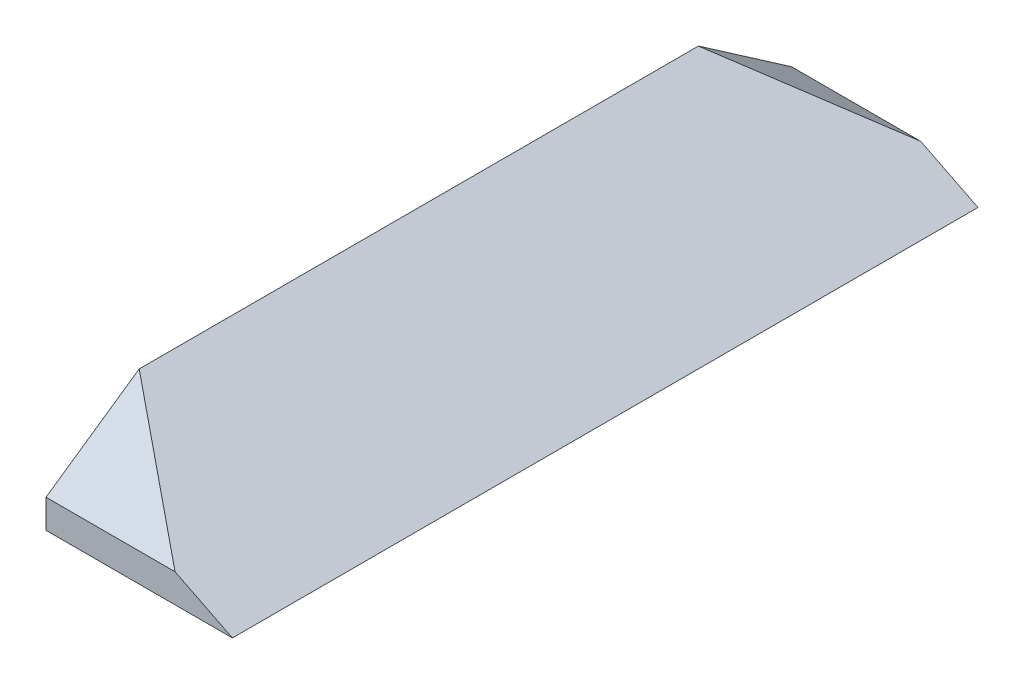
SolidWorks part; units mm, degrees
ref_plane "Front Plane" through (0, 0, 0) normal (0, 0, 1) x (1, 0, 0)
ref_plane "Top Plane" through (0, 0, 0) normal (0, 1, 0) x (1, 0, 0)
ref_plane "Right Plane" through (0, 0, 0) normal (1, 0, 0) x (0, 0, -1)
sketch "Sketch1" plane through (0, 0, 0) normal (0, 0, 1) x (1, 0, 0)
  line L0 (0, 0) -> (10, 0)
  line L1 (10, 0) -> (0, 5)
  line L2 (0, 5) -> (0, 0)
  dimension "D1" = 10
  dimension "D2" = 5
extrude "Boss-Extrude1" add sketch "Sketch1" along normal blind 40
sketch "Sketch3" plane through (0, 0, 0) normal (-1, 0, 0) x (0, 0, 1)
  line L0 (5, 5) -> (0, 1.5376)
  line L1 (40, 5) -> (0, 5) construction
  line L2 (0, 5) -> (0, 0) construction
  line L3 (0, 1.5376) -> (0, 5)
  line L4 (0, 5) -> (5, 5)
  line L9 (35, 5) -> (40, 5)
  line L10 (40, 5) -> (40, 1.5376)
  line L11 (40, 5) -> (40, 0) construction
  line L12 (40, 1.5376) -> (35, 5)
  dimension "D1" = 3.4624
  dimension "D2" = 3.4624
  dimension "D3" = 5
  dimension "D4" = 5
extrude "Cut-Extrude1" cut sketch "Sketch3" against normal blind 30
